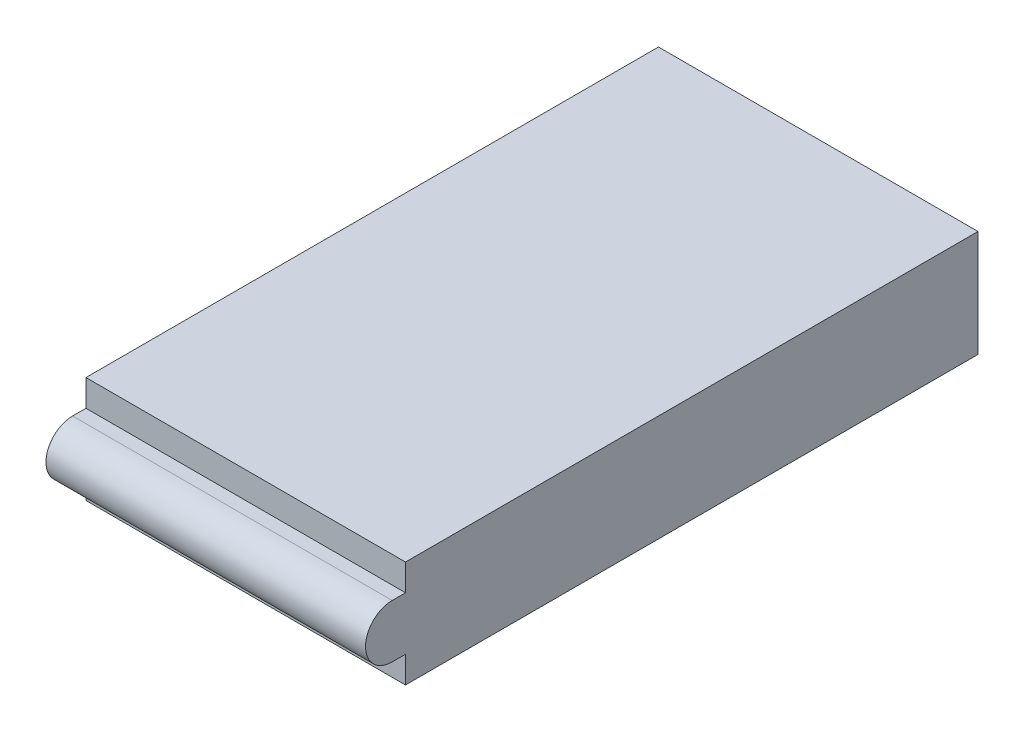
SolidWorks part; units mm, degrees
ref_plane "前视基准面" through (0, 0, 0) normal (0, 0, 1) x (1, 0, 0)
ref_plane "上视基准面" through (0, 0, 0) normal (0, 1, 0) x (1, 0, 0)
ref_plane "右视基准面" through (0, 0, 0) normal (1, 0, 0) x (0, 0, -1)
other "Configuration Table"
sketch "草图1" plane through (0, 0, 0) normal (0, 1, 0) x (1, 0, 0)
  line L1 (0, 0) -> (24, 0)
  line L2 (0, 0) -> (0, 43)
  line L3 (0, 43) -> (24, 43)
  line L4 (24, 0) -> (24, 43)
  line L5 (0, 0) -> (24, 43) construction
  line L6 (0, 43) -> (24, 0) construction
  point P4 (12, 21.5)
  dimension "D1" = 24
  dimension "D2" = 43
extrude "凸台-拉伸1" add sketch "草图1" along normal blind 8
sketch "草图2" plane through (24, 0, 0) normal (1, 0, 0) x (0, 0, -1)
  line L0 (0, 4) -> (-1, 4) construction
  line L1 (0, 8) -> (0, 0) construction
  line L2 (0, 2) -> (-1, 2)
  line L3 (0, 6) -> (-1, 6)
  arc A0 (0, 2) -> (0, 6) centre (0, 4) ccw
  arc A1 (-1, 6) -> (-1, 2) centre (-1, 4) ccw
  point P4 (-0.5, 4)
  point P9 (0, 4)
  point P10 (0, 5.2858)
  dimension "D2" = 2
  dimension "D1" = 1
extrude "凸台-拉伸2" add sketch "草图2" against normal up to surface (24 mm away) up to face at (0, 4, -21.5)
